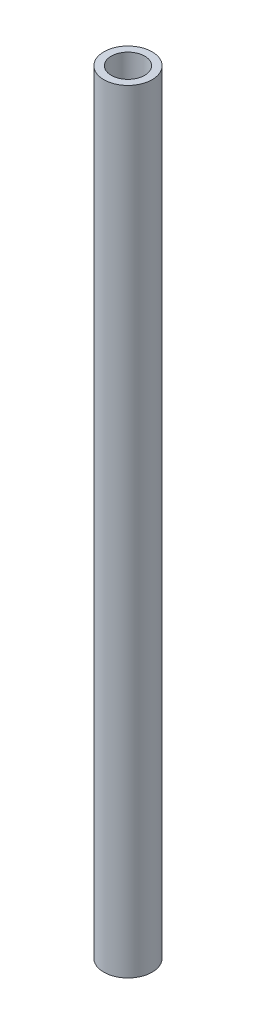
SolidWorks part; units mm, degrees
ref_plane "Front" through (0, 0, 0) normal (0, 0, 1) x (1, 0, 0)
ref_plane "Top" through (0, 0, 0) normal (0, 1, 0) x (1, 0, 0)
ref_plane "Right" through (0, 0, 0) normal (1, 0, 0) x (0, 0, -1)
sketch "Sketch1" plane through (0, 0, 0) normal (0, 1, 0) x (1, 0, 0)
  circle A0 centre (0, 0) radius 3.175
  dimension "D1" = 6.35
extrude "Boss-Extrude1" add sketch "Sketch1" along normal blind 101.6
hole_wizard "Tap Drill for #8 Helicoil1" positions "Sketch2" profile "Sketch3" hole size "#8-32" standard "ANSI Inch"
sketch "Sketch2" plane through (0, 101.6, 0) normal (0, 1, 0) x (1, 0, 0)
  point P0 (0, 0)
sketch "Sketch3" plane through (0, 101.6, 0) normal (1, 0, 0) x (0, 0, 1)
  line L0 (0, 0) -> (0, 102.9192)
  line L1 (0, 102.9192) -> (2.1971, 101.599)
  line L2 (2.1971, 101.599) -> (2.1971, 0)
  line L5 (2.1971, 0) -> (0, 0)
  line L10 (0, 102.9192) -> (-2.1971, 101.599) construction
  line L11 (0, -6.35) -> (0, 107.95) construction
  dimension "Hole Dia." = 4.3942
  dimension "Hole Depth" = 101.599
  dimension "Drill Angle" = 118
